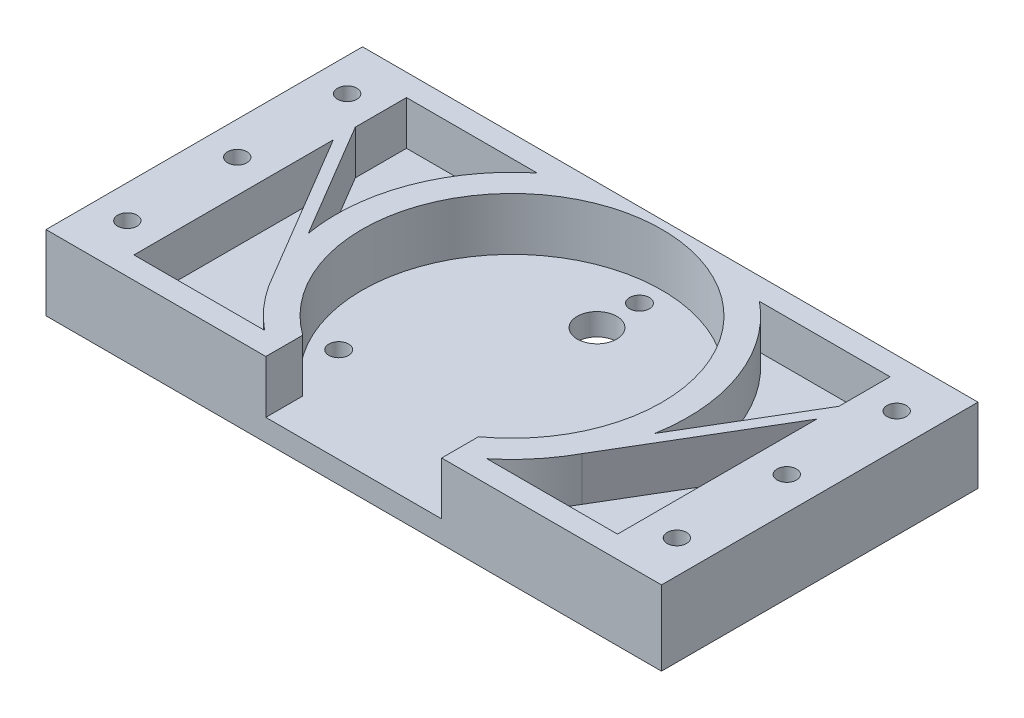
SolidWorks part; units mm, degrees
ref_plane "Front Plane" through (0, 0, 0) normal (0, 0, 1) x (1, 0, 0)
ref_plane "Top Plane" through (0, 0, 0) normal (0, 1, 0) x (1, 0, 0)
ref_plane "Right Plane" through (0, 0, 0) normal (1, 0, 0) x (0, 0, -1)
sketch "Sketch1" plane through (0, 0, 0) normal (0, 1, 0) x (1, 0, 0)
  line L1 (-70, 36) -> (70, 36)
  line L2 (-70, 36) -> (-70, -36)
  line L3 (-70, -36) -> (70, -36)
  line L4 (70, 36) -> (70, -36)
  line L5 (-70, 36) -> (70, -36) construction
  line L6 (-70, -36) -> (70, 36) construction
  point P0 (0, 0)
  dimension "D1" = 72
  dimension "D2" = 140
extrude "Boss-Extrude1" add sketch "Sketch1" along normal blind 17
sketch "Sketch2" plane through (0, 17, 0) normal (0, 1, 0) x (1, 0, 0)
  circle A0 centre (0, 0) radius 34.1
  dimension "D1" = 68.2
extrude "Cut-Extrude1" cut sketch "Sketch2" against normal blind 12
sketch "Sketch3" plane through (0, 0, 36) normal (0, 0, 1) x (1, 0, 0)
  line L0 (-70, 17) -> (70, 17) construction
  line L1 (-20, 29) -> (20, 29)
  line L2 (-20, 29) -> (-20, 5)
  line L3 (-20, 5) -> (20, 5)
  line L4 (20, 29) -> (20, 5)
  line L5 (-20, 29) -> (20, 5) construction
  line L6 (-20, 5) -> (20, 29) construction
  point P0 (0, 17)
  point P7 (20, 17)
  dimension "D1" = 12
  dimension "D2" = 40
extrude "Cut-Extrude2" cut sketch "Sketch3" against normal blind 10
sketch "Sketch4" plane through (0, 17, 0) normal (0, 1, 0) x (1, 0, 0)
  line L0 (-15.95, 0) -> (15.95, 0) construction
  line L1 (-70, 36) -> (-70, -36) construction
  line L2 (0, -15.95) -> (0, 15.95) construction
  circle A0 centre (-62.5, 25) radius 2.2
  circle A1 centre (-62.5, 0) radius 2.2
  circle A2 centre (-62.5, -25) radius 2.2
  circle A3 centre (62.5, -25) radius 2.2
  circle A4 centre (62.5, 0) radius 2.2
  circle A5 centre (62.5, 25) radius 2.2
  point P8 (0, 0)
  point P10 (-66.8793, 3.2361)
  dimension "D4" = 4.4
  dimension "D5" = 4.4
  dimension "D6" = 4.4
  dimension "D1" = 25
  dimension "D2" = 25
  dimension "D3" = 7.5
extrude "Cut-Extrude3" cut sketch "Sketch4" against normal through all
sketch "Sketch5" plane through (0, 5, 0) normal (0, 1, 0) x (1, 0, 0)
  line L0 (0, -9.35) -> (0, 9.35) construction
  circle A0 centre (0, 29) radius 2.25
  circle A1 centre (25.0423, -14.3746) radius 2.25
  circle A2 centre (-25.0423, -14.3746) radius 2.25
  circle A3 centre (0, 19.3336) radius 4.5
  point P12 (0, 0.0836)
  dimension "D1" = 4.5
  dimension "D5" = 9
  dimension "D2" = 29
  dimension "D4" = 19.25
  dimension "D3" = 3
extrude "Cut-Extrude4" cut sketch "Sketch5" against normal through all
sketch "Sketch6" plane through (0, 17, 0) normal (0, 1, 0) x (1, 0, 0)
  line L7 (-55, 0) -> (-55, 14.355) construction
  line L8 (-9.35, 0) -> (9.35, 0) construction
  line L9 (-55, 46.2181) -> (-55, 19.355) construction
  line L10 (-55, -31) -> (-25.2784, -31) construction
  line L11 (-55, 31) -> (-25.2784, 31)
  line L12 (-55, 31) -> (-55, 19.355)
  line L13 (-55, -31) -> (-25.2784, -31)
  line L14 (70, 36) -> (-70, 36) construction
  line L15 (-70, 36) -> (-70, -36) construction
  line L16 (-70, -36) -> (-20, -36) construction
  line L17 (0, -9.35) -> (0, 9.35) construction
  line L18 (55, -31) -> (25.2784, -31)
  line L19 (55, 31) -> (55, 19.355)
  line L20 (55, 31) -> (25.2784, 31)
  line L21 (-55, 14.355) -> (-35.0938, -19.1945)
  line L22 (-55, 19.355) -> (-39.3913, -6.9515)
  line L23 (-55, 19.355) -> (-55, 46.2181) construction
  line L24 (-55, 14.355) -> (-55, -31)
  line L25 (-55, 14.355) -> (-55, -31) construction
  line L26 (55, 14.355) -> (35.0938, -19.1945)
  line L27 (55, 19.355) -> (39.3913, -6.9515)
  line L28 (55, 14.355) -> (55, -31)
  arc A1 (-25.2784, 31) -> (-39.3913, -6.9515) centre (0, 0) ccw
  arc A2 (25.2784, -31) -> (35.0938, -19.1945) centre (0, 0) ccw
  arc A3 (-35.0938, -19.1945) -> (-25.2784, -31) centre (0, 0) ccw
  arc A4 (39.3913, -6.9515) -> (25.2784, 31) centre (0, 0) ccw
  dimension "D1" = 80
  dimension "D2" = 5
  dimension "D3" = 15
  dimension "D4" = 5
  dimension "D5" = 5
  dimension "D6" = 0
extrude "Cut-Extrude5" cut sketch "Sketch6" against normal blind 10
equation "\"D5@Sketch4\"=\"D4@Sketch4\""
equation "\"D6@Sketch4\"=\"D5@Sketch4\""
